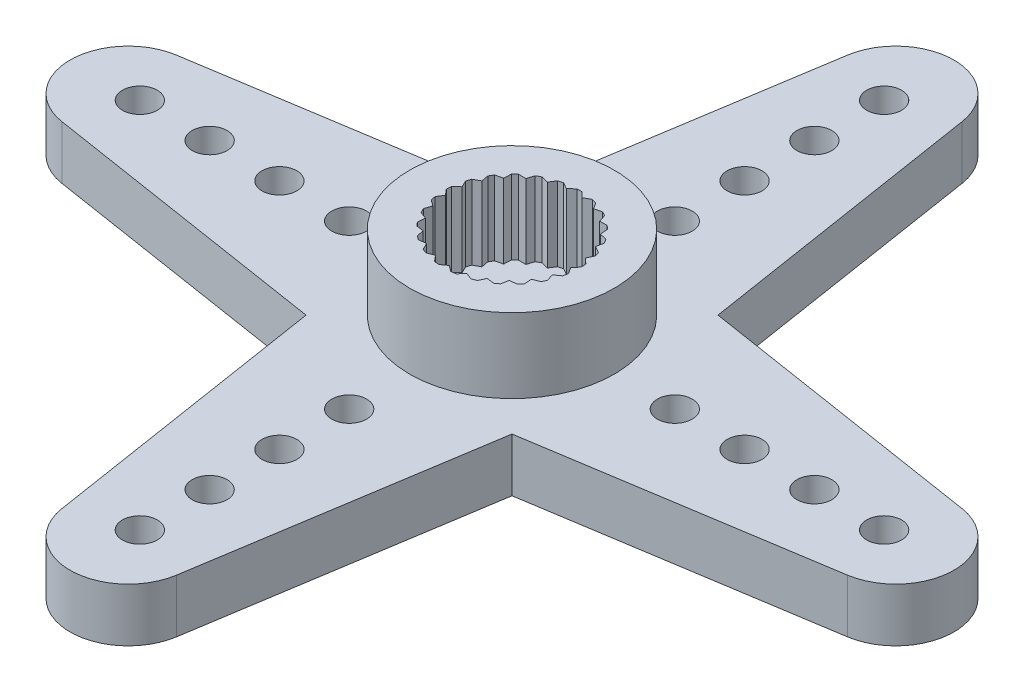
SolidWorks part; units mm, degrees
material "ABS"
ref_plane "Front Plane" through (0, 0, 0) normal (0, 0, 1) x (1, 0, 0)
ref_plane "Top Plane" through (0, 0, 0) normal (0, 1, 0) x (1, 0, 0)
ref_plane "Right Plane" through (0, 0, 0) normal (1, 0, 0) x (0, 0, -1)
sketch "Sketch2" plane through (0, 0, 0) normal (0, 1, 0) x (1, 0, 0)
  circle A0 centre (0, 0) radius 6
  circle A1 centre (0, 0) radius 1.5
  dimension "D1" = 12
  dimension "D2" = 3
extrude "Boss-Extrude1" add sketch "Sketch2" along normal mid plane 2.3
sketch "Sketch3" plane through (0, 1.15, 0) normal (0, 1, 0) x (1, 0, 0)
  line L0 (0, 0) -> (0, 2.9) construction
  line L3 (0, 0) -> (0.376, 2.9763) construction
  line L52 (0.1074, 2.898) -> (0.3384, 2.6787)
  line L53 (-0.1074, 2.898) -> (-0.3384, 2.6787)
  line L54 (0.8248, 2.7802) -> (0.9939, 2.5104)
  line L55 (0.6167, 2.8337) -> (0.3384, 2.6787)
  line L56 (1.4903, 2.4878) -> (1.587, 2.1843)
  line L57 (1.302, 2.5913) -> (0.9939, 2.5104)
  line L58 (2.0621, 2.039) -> (2.0804, 1.721)
  line L59 (1.9055, 2.1861) -> (1.587, 2.1843)
  line L60 (2.5044, 1.4621) -> (2.443, 1.1496)
  line L61 (2.3893, 1.6435) -> (2.0804, 1.721)
  line L62 (2.7894, 0.7934) -> (2.6522, 0.5059)
  line L63 (2.723, 0.9977) -> (2.443, 1.1496)
  line L64 (2.899, 0.0748) -> (2.6947, -0.1695)
  line L65 (2.8855, 0.2892) -> (2.6522, 0.5059)
  line L66 (2.8265, -0.6486) -> (2.5679, -0.8343)
  line L67 (2.8668, -0.4375) -> (2.6947, -0.1695)
  line L68 (2.5765, -1.3311) -> (2.2797, -1.4467)
  line L69 (2.6679, -1.1367) -> (2.5679, -0.8343)
  line L70 (2.1645, -1.93) -> (1.8483, -1.9682)
  line L71 (2.3014, -1.7645) -> (2.2797, -1.4467)
  line L72 (1.6165, -2.4077) -> (1.3007, -2.366)
  line L73 (1.7903, -2.2814) -> (1.8483, -1.9682)
  line L74 (0.967, -2.734) -> (0.6715, -2.6152)
  line L75 (1.1667, -2.655) -> (1.3007, -2.366)
  line L76 (0.2566, -2.8886) -> (0, -2.7)
  line L77 (0.4698, -2.8617) -> (0.6715, -2.6152)
  line L78 (-0.4698, -2.8617) -> (-0.6715, -2.6152)
  line L79 (-0.2566, -2.8886) -> (0, -2.7)
  line L80 (-1.1667, -2.655) -> (-1.3007, -2.366)
  line L81 (-0.967, -2.734) -> (-0.6715, -2.6152)
  line L82 (-1.7903, -2.2814) -> (-1.8483, -1.9682)
  line L83 (-1.6165, -2.4077) -> (-1.3007, -2.366)
  line L84 (-2.3014, -1.7645) -> (-2.2797, -1.4467)
  line L85 (-2.1645, -1.93) -> (-1.8483, -1.9682)
  line L86 (-2.6679, -1.1367) -> (-2.5679, -0.8343)
  line L87 (-2.5765, -1.3311) -> (-2.2797, -1.4467)
  line L88 (-2.8668, -0.4375) -> (-2.6947, -0.1695)
  line L89 (-2.8265, -0.6486) -> (-2.5679, -0.8343)
  line L90 (-2.8855, 0.2892) -> (-2.6522, 0.5059)
  line L91 (-2.899, 0.0748) -> (-2.6947, -0.1695)
  line L92 (-2.723, 0.9977) -> (-2.443, 1.1496)
  line L93 (-2.7894, 0.7934) -> (-2.6522, 0.5059)
  line L94 (-2.3893, 1.6435) -> (-2.0804, 1.721)
  line L95 (-2.5044, 1.4621) -> (-2.443, 1.1496)
  line L96 (-1.9055, 2.1861) -> (-1.587, 2.1843)
  line L97 (-2.0621, 2.039) -> (-2.0804, 1.721)
  line L98 (-1.302, 2.5913) -> (-0.9939, 2.5104)
  line L99 (-1.4903, 2.4878) -> (-1.587, 2.1843)
  line L100 (-0.6167, 2.8337) -> (-0.3384, 2.6787)
  line L101 (-0.8248, 2.7802) -> (-0.9939, 2.5104)
  line L102 (-2.533, 1.6075) -> (-2.3893, 1.6435) construction
  line L103 (-2.533, 1.6075) -> (-2.5044, 1.4621) construction
  line L104 (-2.8532, 0.9271) -> (-2.723, 0.9977) construction
  line L105 (-2.8532, 0.9271) -> (-2.7894, 0.7934) construction
  line L106 (-2.9941, 0.1884) -> (-2.8855, 0.2892) construction
  line L107 (-2.9941, 0.1884) -> (-2.899, 0.0748) construction
  line L108 (-2.9469, -0.5621) -> (-2.8668, -0.4375) construction
  line L109 (-2.9469, -0.5621) -> (-2.8265, -0.6486) construction
  line L110 (0, 3) -> (0.1074, 2.898) construction
  line L111 (0, 2.9) -> (0, 3) construction
  line L112 (0, 3) -> (-0.1074, 2.898) construction
  line L113 (-0.7461, 2.9057) -> (-0.6167, 2.8337) construction
  line L114 (-0.7461, 2.9057) -> (-0.8248, 2.7802) construction
  line L115 (-1.4453, 2.6289) -> (-1.302, 2.5913) construction
  line L116 (-1.4453, 2.6289) -> (-1.4903, 2.4878) construction
  line L117 (-2.0536, 2.1869) -> (-1.9055, 2.1861) construction
  line L118 (-2.0536, 2.1869) -> (-2.0621, 2.039) construction
  line L119 (-2.7145, -1.2773) -> (-2.6679, -1.1367) construction
  line L120 (-2.7145, -1.2773) -> (-2.5765, -1.3311) construction
  line L121 (-2.3115, -1.9123) -> (-2.3014, -1.7645) construction
  line L122 (-2.3115, -1.9123) -> (-2.1645, -1.93) construction
  line L123 (-1.7634, -2.4271) -> (-1.7903, -2.2814) construction
  line L124 (-1.7634, -2.4271) -> (-1.6165, -2.4077) construction
  line L125 (-1.1044, -2.7893) -> (-1.1667, -2.655) construction
  line L126 (-1.1044, -2.7893) -> (-0.967, -2.734) construction
  line L127 (-0.376, -2.9763) -> (-0.4698, -2.8617) construction
  line L128 (-0.376, -2.9763) -> (-0.2566, -2.8886) construction
  line L129 (0.376, -2.9763) -> (0.2566, -2.8886) construction
  line L130 (0.376, -2.9763) -> (0.4698, -2.8617) construction
  line L131 (1.1044, -2.7893) -> (0.967, -2.734) construction
  line L132 (1.1044, -2.7893) -> (1.1667, -2.655) construction
  line L133 (1.7634, -2.4271) -> (1.6165, -2.4077) construction
  line L134 (1.7634, -2.4271) -> (1.7903, -2.2814) construction
  line L135 (2.3115, -1.9123) -> (2.3014, -1.7645) construction
  line L136 (2.3115, -1.9123) -> (2.1645, -1.93) construction
  line L137 (2.7145, -1.2773) -> (2.6679, -1.1367) construction
  line L138 (2.7145, -1.2773) -> (2.5765, -1.3311) construction
  line L139 (2.9469, -0.5621) -> (2.8668, -0.4375) construction
  line L140 (2.9469, -0.5621) -> (2.8265, -0.6486) construction
  line L141 (2.9941, 0.1884) -> (2.8855, 0.2892) construction
  line L142 (2.9941, 0.1884) -> (2.899, 0.0748) construction
  line L143 (2.8532, 0.9271) -> (2.723, 0.9977) construction
  line L144 (2.8532, 0.9271) -> (2.7894, 0.7934) construction
  line L145 (2.533, 1.6075) -> (2.3893, 1.6435) construction
  line L146 (2.533, 1.6075) -> (2.5044, 1.4621) construction
  line L147 (2.0536, 2.1869) -> (1.9055, 2.1861) construction
  line L148 (2.0536, 2.1869) -> (2.0621, 2.039) construction
  line L149 (1.4453, 2.6289) -> (1.302, 2.5913) construction
  line L150 (1.4453, 2.6289) -> (1.4903, 2.4878) construction
  line L151 (0.7461, 2.9057) -> (0.6167, 2.8337) construction
  line L152 (0.7461, 2.9057) -> (0.8248, 2.7802) construction
  circle A0 centre (0, 0) radius 4.4
  circle A1 centre (0, 0) radius 3 construction
  circle A2 centre (0, 0) radius 2.7 construction
  arc A3 (-0.6167, 2.8337) -> (-0.8248, 2.7802) centre (0, 0) ccw
  arc A4 (-0.1074, 2.898) -> (-0.6167, 2.8337) centre (0, 0) ccw construction
  arc A5 (-0.8248, 2.7802) -> (-1.302, 2.5913) centre (0, 0) ccw construction
  arc A6 (-1.302, 2.5913) -> (-1.4903, 2.4878) centre (0, 0) ccw
  arc A7 (-1.4903, 2.4878) -> (-1.9055, 2.1861) centre (0, 0) ccw construction
  arc A8 (-1.9055, 2.1861) -> (-2.0621, 2.039) centre (0, 0) ccw
  arc A9 (-2.0621, 2.039) -> (-2.3893, 1.6435) centre (0, 0) ccw construction
  arc A10 (-2.3893, 1.6435) -> (-2.5044, 1.4621) centre (0, 0) ccw
  arc A11 (-2.5044, 1.4621) -> (-2.723, 0.9977) centre (0, 0) ccw construction
  arc A12 (-2.723, 0.9977) -> (-2.7894, 0.7934) centre (0, 0) ccw
  arc A13 (-2.7894, 0.7934) -> (-2.8855, 0.2892) centre (0, 0) ccw construction
  arc A14 (-2.8855, 0.2892) -> (-2.899, 0.0748) centre (0, 0) ccw
  arc A15 (-2.899, 0.0748) -> (-2.8668, -0.4375) centre (0, 0) ccw construction
  arc A16 (-2.8668, -0.4375) -> (-2.8265, -0.6486) centre (0, 0) ccw
  arc A17 (-2.8265, -0.6486) -> (-2.6679, -1.1367) centre (0, 0) ccw construction
  arc A18 (-2.6679, -1.1367) -> (-2.5765, -1.3311) centre (0, 0) ccw
  arc A19 (-2.5765, -1.3311) -> (-2.3014, -1.7645) centre (0, 0) ccw construction
  arc A20 (-2.3014, -1.7645) -> (-2.1645, -1.93) centre (0, 0) ccw
  arc A21 (-2.1645, -1.93) -> (-1.7903, -2.2814) centre (0, 0) ccw construction
  arc A22 (-1.7903, -2.2814) -> (-1.6165, -2.4077) centre (0, 0) ccw
  arc A23 (-1.6165, -2.4077) -> (-1.1667, -2.655) centre (0, 0) ccw construction
  arc A24 (-1.1667, -2.655) -> (-0.967, -2.734) centre (0, 0) ccw
  arc A25 (-0.967, -2.734) -> (-0.4698, -2.8617) centre (0, 0) ccw construction
  arc A26 (-0.4698, -2.8617) -> (-0.2566, -2.8886) centre (0, 0) ccw
  arc A27 (-0.2566, -2.8886) -> (0.2566, -2.8886) centre (0, 0) ccw construction
  arc A28 (0.2566, -2.8886) -> (0.4698, -2.8617) centre (0, 0) ccw
  arc A29 (0.4698, -2.8617) -> (0.967, -2.734) centre (0, 0) ccw construction
  arc A30 (0.967, -2.734) -> (1.1667, -2.655) centre (0, 0) ccw
  arc A31 (1.1667, -2.655) -> (1.6165, -2.4077) centre (0, 0) ccw construction
  arc A32 (1.6165, -2.4077) -> (1.7903, -2.2814) centre (0, 0) ccw
  arc A33 (1.7903, -2.2814) -> (2.1645, -1.93) centre (0, 0) ccw construction
  arc A34 (2.1645, -1.93) -> (2.3014, -1.7645) centre (0, 0) ccw
  arc A35 (2.3014, -1.7645) -> (2.5765, -1.3311) centre (0, 0) ccw construction
  arc A36 (2.5765, -1.3311) -> (2.6679, -1.1367) centre (0, 0) ccw
  arc A37 (2.6679, -1.1367) -> (2.8265, -0.6486) centre (0, 0) ccw construction
  arc A38 (2.8265, -0.6486) -> (2.8668, -0.4375) centre (0, 0) ccw
  arc A39 (2.8668, -0.4375) -> (2.899, 0.0748) centre (0, 0) ccw construction
  arc A40 (2.899, 0.0748) -> (2.8855, 0.2892) centre (0, 0) ccw
  arc A41 (2.8855, 0.2892) -> (2.7894, 0.7934) centre (0, 0) ccw construction
  arc A42 (2.7894, 0.7934) -> (2.723, 0.9977) centre (0, 0) ccw
  arc A43 (2.723, 0.9977) -> (2.5044, 1.4621) centre (0, 0) ccw construction
  arc A44 (2.5044, 1.4621) -> (2.3893, 1.6435) centre (0, 0) ccw
  arc A45 (2.3893, 1.6435) -> (2.0621, 2.039) centre (0, 0) ccw construction
  arc A46 (2.0621, 2.039) -> (1.9055, 2.1861) centre (0, 0) ccw
  arc A47 (1.9055, 2.1861) -> (1.4903, 2.4878) centre (0, 0) ccw construction
  arc A48 (1.4903, 2.4878) -> (1.302, 2.5913) centre (0, 0) ccw
  arc A49 (1.302, 2.5913) -> (0.8248, 2.7802) centre (0, 0) ccw construction
  arc A50 (0.8248, 2.7802) -> (0.6167, 2.8337) centre (0, 0) ccw
  arc A51 (0.3635, 2.8771) -> (0.1074, 2.898) centre (0, 0) ccw construction
  arc A52 (0.1074, 2.898) -> (-0.1074, 2.898) centre (0, 0) ccw
  arc A53 (0.6167, 2.8337) -> (0.3635, 2.8771) centre (0, 0) ccw construction
  point P84 (0, 0)
  dimension "D1" = 8.8
  dimension "D2" = 5.4
  dimension "D3" = 6
  dimension "D6" = 5.8
  dimension "D4" = 7.2
  dimension "D5" = 25
extrude "Boss-Extrude2" add sketch "Sketch3" along normal blind 3.2
sketch "Sketch4" plane through (0, 0, 0) normal (0, 1, 0) x (1, 0, 0)
  line L0 (0, 0) -> (16, 0) construction
  line L1 (3.9686, 4.5) -> (16.8881, 2.4697)
  line L2 (3.9686, -4.5) -> (16.8881, -2.4697)
  line L3 (16, 0) -> (13, 0) construction
  circle A0 centre (0, 0) radius 6 construction
  arc A1 (3.9686, -4.5) -> (3.9686, 4.5) centre (0, 0) ccw
  arc A2 (16.8881, 2.4697) -> (16.8881, -2.4697) centre (16.5, 0) cw
  circle A3 centre (16, 0) radius 0.75
  circle A4 centre (13, 0) radius 0.75
  circle A5 centre (10, 0) radius 0.75
  circle A6 centre (7, 0) radius 0.75
  dimension "D3" = 2.5
  dimension "D5" = 1.5
  dimension "D2" = 9
  dimension "D7" = 3
  dimension "D4" = 0.5
  dimension "D1" = 16
  dimension "D6" = 4
extrude "Boss-Extrude3" add sketch "Sketch4" along normal mid plane 2.3
pattern_circular "CirPattern1" count 4 over 360 about axis through (0, 0, 0) along (0, 1, 0) of "Boss-Extrude3"
sketch "Sketch5" [suppressed] plane through (0, 0, 0) normal (0, 1, 0) x (1, 0, 0)
  line L0 (3, 7) -> (-3, 7) construction
  circle A0 centre (0, 0) radius 10
  circle A1 centre (0, 7) radius 0.75
  circle A2 centre (-3, 7) radius 0.75
  circle A3 centre (3, 7) radius 0.75
  circle A4 centre (7, 3) radius 0.75
  circle A5 centre (7, 0) radius 0.75
  circle A6 centre (7, -3) radius 0.75
  circle A7 centre (3, -7) radius 0.75
  circle A8 centre (0, -7) radius 0.75
  circle A9 centre (-3, -7) radius 0.75
  circle A10 centre (-7, -3) radius 0.75
  circle A11 centre (-7, 0) radius 0.75
  circle A12 centre (-7, 3) radius 0.75
  circle A13 centre (0, 0) radius 1.5 construction
  circle A14 centre (0, 0) radius 1.5
  point P8 (0, 7)
  point P31 (0, 0)
  dimension "D1" = 1.5
  dimension "D3" = 2.25
  dimension "D4" = 6
  dimension "D2" = 7
  dimension "D5" = 4
extrude "Boss-Extrude4" [suppressed] add sketch "Sketch5" along normal mid plane 2.3
equation "\"N_hole\"= 4"
equation "\"N_horn\"= 4"
equation "\"D6@Sketch4\"=\"N_hole\""
equation "\"D1@CirPattern1\"=\"N_horn\""
equation "\"D1@Sketch4\"=(\"N_hole\" - 1) *3 +7"
